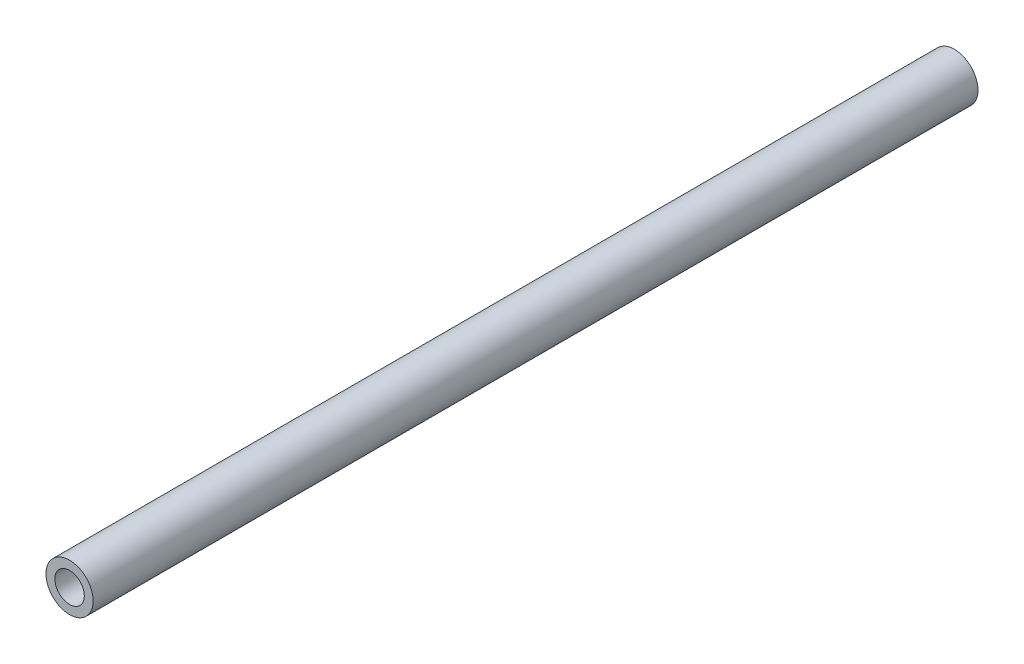
SolidWorks part; units mm, degrees
material "Thornel Mat VMA"
ref_plane "前视基准面" through (0, 0, 0) normal (0, 0, 1) x (1, 0, 0)
ref_plane "上视基准面" through (0, 0, 0) normal (0, 1, 0) x (1, 0, 0)
ref_plane "右视基准面" through (0, 0, 0) normal (1, 0, 0) x (0, 0, -1)
other "Configuration Table"
sketch "草图1" plane through (0, 0, 0) normal (0, 0, 1) x (1, 0, 0)
  circle A0 centre (0, 0) radius 4
extrude "凸台-拉伸1" add sketch "草图1" along normal blind 150
sketch "草图2" plane through (0, 0, 150) normal (0, 0, 1) x (1, 0, 0)
  circle A0 centre (0, 0) radius 2.5
extrude "切除-拉伸1" cut sketch "草图2" against normal blind 330
